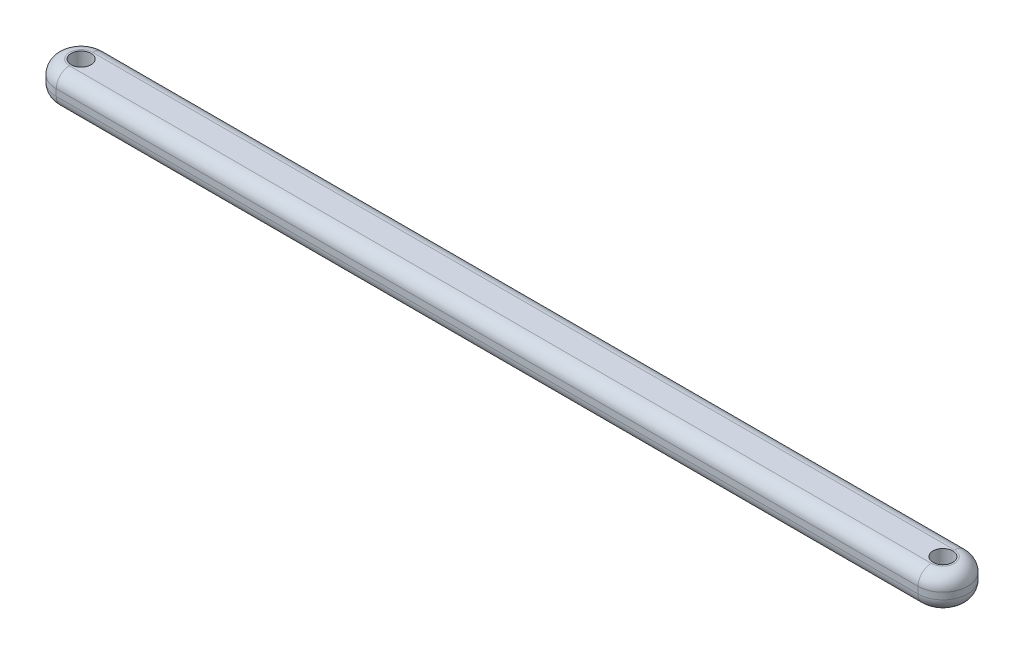
SolidWorks part; units mm, degrees
material "ABS PC"
ref_plane "Alzado" through (0, 0, 0) normal (1, 0, 0) x (0, 1, 0)
ref_plane "Planta" through (0, 0, 0) normal (0, 0, 1) x (0, 1, 0)
ref_plane "Vista lateral" through (0, 0, 0) normal (0, 1, 0) x (-1, 0, 0)
sketch "Croquis1" plane through (0, 0, 0) normal (0, 1, 0) x (-1, 0, 0)
  line L0 (0, 0) -> (260, 0) construction
  line L6 (0, -7.5) -> (260, -7.5)
  line L8 (260, 7.5) -> (0, 7.5)
  line L9 (130, -7.5) -> (130, 0) construction
  circle A0 centre (0, 0) radius 3
  circle A1 centre (260, 0) radius 3
  arc A3 (260, -7.5) -> (267.5, 0) centre (260, 0) ccw construction
  arc A9 (260, -7.5) -> (267.5, 0) centre (260, 0) ccw construction
  arc A10 (260, -7.5) -> (260, 7.5) centre (260, 0) ccw
  arc A12 (0, -7.5) -> (0, 7.5) centre (0, 0) cw
  dimension "D3" = 6
  dimension "D1" = 260
  dimension "D2" = 15
extrude "Saliente-Extruir1" add sketch "Croquis1" along normal mid plane 10
fillet "Redondeo3" radius 4 8 edges at (-267.5, 5, 0) (-267.5, -5, 0) (-130, 5, 7.5) (-130, -5, 7.5) (7.5, 5, 0) (7.5, -5, 0) (-130, 5, -7.5) (-130, -5, -7.5)
equation "\"L1\"=250"
equation "\"ancho\"= 15"
equation "\"esp\"= 10"
equation "\"agujeros\"= 6"
equation "\"L2\"=260"
equation "\"D1@Croquis1\"=\"L2\""
equation "\"D2@Croquis1\"=\"ancho\""
equation "\"D3@Croquis1\"=\"agujeros\""
equation "\"D1@Saliente-Extruir1\"=\"esp\""
